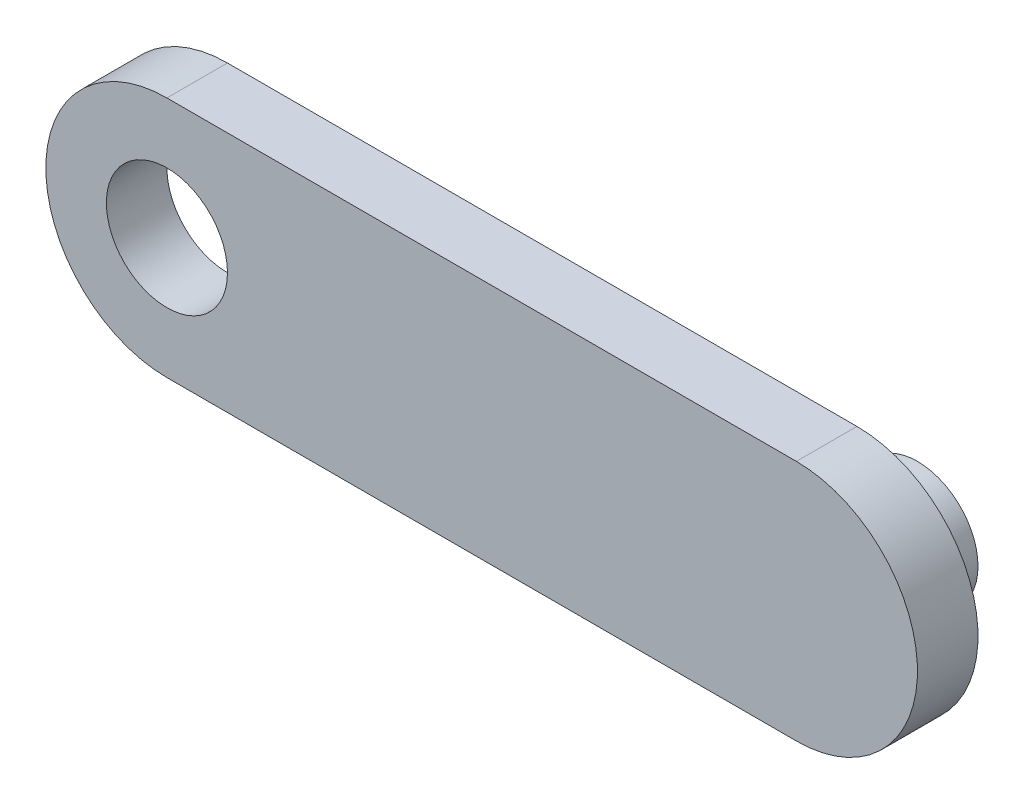
SolidWorks part; units mm, degrees
ref_plane "정면" through (0, 0, 0) normal (0, 0, 1) x (1, 0, 0)
ref_plane "윗면" through (0, 0, 0) normal (0, 1, 0) x (1, 0, 0)
ref_plane "우측면" through (0, 0, 0) normal (1, 0, 0) x (0, 0, -1)
sketch "스케치1" plane through (0, 0, 0) normal (0, 0, 1) x (1, 0, 0)
  line L1 (0, 20) -> (103.9598, 20)
  line L3 (0, -20) -> (103.9598, -20)
  circle A0 centre (0, 0) radius 10
  arc A1 (0, 20) -> (0, -20) centre (0, 0) ccw
  arc A2 (103.9598, -20) -> (103.9598, 20) centre (103.9598, 0) ccw
extrude "보스-돌출1" add sketch "스케치1" along normal blind 10
sketch "스케치2" plane through (0, 0, 0) normal (0, 0, -1) x (-1, 0, 0)
  circle A0 centre (-103.9598, 0) radius 10
extrude "보스-돌출2" add sketch "스케치2" along normal blind 10
